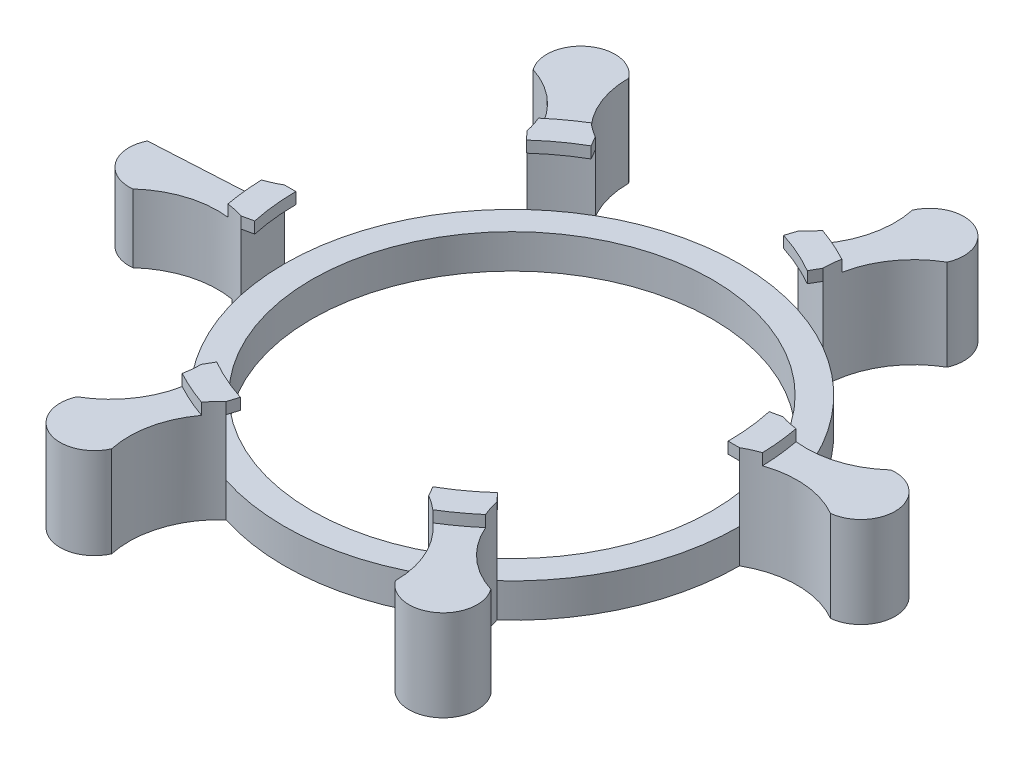
SolidWorks part; units mm, degrees
ref_plane "Front Plane" through (0, 0, 0) normal (0, 0, 1) x (1, 0, 0)
ref_plane "Top Plane" through (0, 0, 0) normal (0, 1, 0) x (1, 0, 0)
ref_plane "Right Plane" through (0, 0, 0) normal (1, 0, 0) x (0, 0, -1)
sketch "Sketch1" plane through (0, 0, 0) normal (0, 1, 0) x (1, 0, 0)
  circle A0 centre (0, 0) radius 63.5
  circle A1 centre (0, 0) radius 55.88
extrude "Boss-Extrude1" add sketch "Sketch1" along normal blind 9.525
sketch "Sketch2" plane through (0, 9.525, 0) normal (0, 1, 0) x (1, 0, 0)
  arc A0 (62.0421, 13.5288) -> (86.8589, 18.9403) centre (69.764, 37.7266) ccw
  arc A1 (63.5, 0) -> (88.9, 0) centre (76.2, -21.997) cw
  circle A2 centre (0, 0) radius 63.5 construction
  arc A4 (88.9, 0) -> (86.8589, 18.9403) centre (87.8795, 9.4702) ccw
  arc A5 (63.5, 0) -> (62.0421, 13.5288) centre (0, 0) ccw
extrude "Boss-Extrude2" add sketch "Sketch2" against normal blind 9.525 and the other way blind 15.875
sketch "Sketch3" plane through (0, 25.4, 0) normal (0, 1, 0) x (1, 0, 0)
  line L0 (60.325, 0) -> (63.5, 0)
  line L1 (58.94, 12.8524) -> (62.0421, 13.5288)
  arc A0 (67.9151, 2.0138) -> (66.7849, 12.5019) centre (0, 0) ccw
  arc A1 (60.325, 0) -> (58.94, 12.8524) centre (0, 0) ccw
  arc A2 (63.5, 0) -> (67.9151, 2.0138) centre (76.2, -21.997) cw
  arc A3 (62.0421, 13.5288) -> (66.7849, 12.5019) centre (69.764, 37.7266) ccw
  arc A4 (62.0421, 13.5288) -> (86.8589, 18.9403) centre (69.764, 37.7266) ccw construction
  arc A5 (63.5, 0) -> (62.0421, 13.5288) centre (0, 0) ccw construction
extrude "Boss-Extrude3" add sketch "Sketch3" along normal blind 3.175
pattern_circular "CirPattern1" count 6 over 360 about axis through (0, 0, 0) along (0, 1, 0) of bodies 103
sketch "Sketch7" plane through (0, 0, 0) normal (0, -1, 0) x (-1, 0, 0)
  line L0 (63.5, 0) -> (67.5691, -7.5772)
  line L1 (63.5, 0) -> (88.9, 0)
  line L5 (88.9, 0) -> (97.9133, 0)
  line L6 (67.5691, -7.5772) -> (97.3496, -10.4907)
  arc A1 (97.3496, -10.4907) -> (97.9133, 0) centre (0, 0) ccw
  arc A6 (86.8589, -18.9403) -> (88.9, 0) centre (87.8795, -9.4702) ccw construction
extrude "Boss-Extrude7" add sketch "Sketch7" against normal blind 9.525
sketch "Sketch9" plane through (0, 0, 0) normal (0, -1, 0) x (-1, 0, 0)
  line L0 (61.3965, -26.0005) -> (106.9556, -39.5314)
  line L1 (106.9556, -39.5314) -> (132.962, 11.0168)
  line L2 (132.962, 11.0168) -> (94.7143, 43.8427)
  line L3 (94.7143, 43.8427) -> (63.3326, 20.8455)
  arc A1 (61.3965, -26.0005) -> (63.3326, 20.8455) centre (0, 0) ccw
extrude "Cut-Extrude5" cut sketch "Sketch9" against normal blind 6.35
sketch "Sketch11" plane through (0, 25.4, 0) normal (0, 1, 0) x (1, 0, 0)
  line L0 (-67.8425, -3.7316) -> (-122.8401, -6.7566)
  line L1 (-122.8401, -6.7566) -> (-98.142, 22.2877)
  line L2 (-98.142, 22.2877) -> (-66.4604, 14.1258)
  arc A0 (-66.4604, 14.1258) -> (-67.8425, -3.7316) centre (0, 0) ccw
extrude "Cut-Extrude8" cut sketch "Sketch11" against normal up to surface (15.875 mm away) up to face at (0, 9.525, 0)
sketch "Sketch12" plane through (0, 6.35, 0) normal (0, -1, 0) x (1, 0, 0)
  line L0 (-69.2003, 2.5237) -> (-95.0015, 2.5237) construction
  line L1 (-69.2003, 1.3807) -> (-95.0015, 1.3807)
  line L2 (-69.2003, 3.6668) -> (-95.0015, 3.6668)
  arc A0 (-69.2003, 1.3807) -> (-69.2003, 3.6668) centre (-69.2003, 2.5237) ccw
  arc A1 (-95.0015, 3.6668) -> (-95.0015, 1.3807) centre (-95.0015, 2.5237) ccw
  point P2 (-82.1009, 2.5237)
extrude "Cut-Extrude10" cut sketch "Sketch12" against normal blind 10.414
